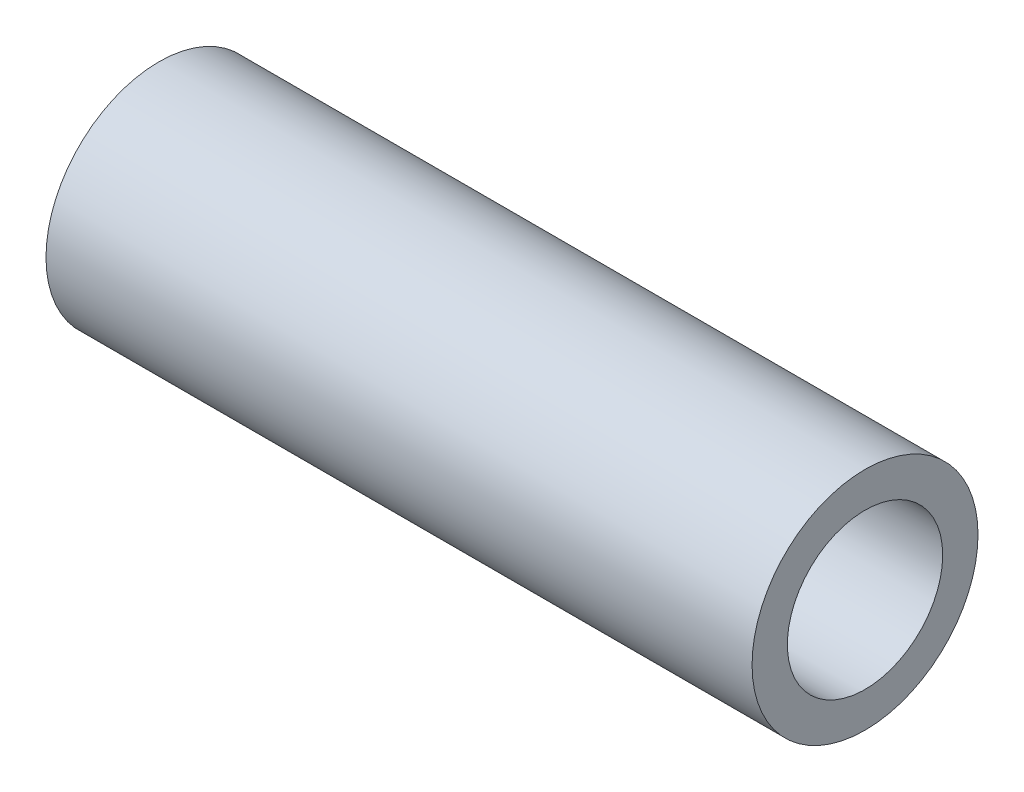
SolidWorks part; units mm, degrees
material "Alumina"
ref_plane "Front Plane" through (0, 0, 0) normal (0, 0, 1) x (1, 0, 0)
ref_plane "Top Plane" through (0, 0, 0) normal (0, 1, 0) x (1, 0, 0)
ref_plane "Right Plane" through (0, 0, 0) normal (1, 0, 0) x (0, 0, -1)
sketch "Sketch1" plane through (0, 0, 0) normal (1, 0, 0) x (0, 0, -1)
  circle A0 centre (0, 0) radius 4
  circle A1 centre (0, 0) radius 2.75
  dimension "D1" = 8
  dimension "D2" = 5.5
extrude "Boss-Extrude1" add sketch "Sketch1" along normal mid plane 25
